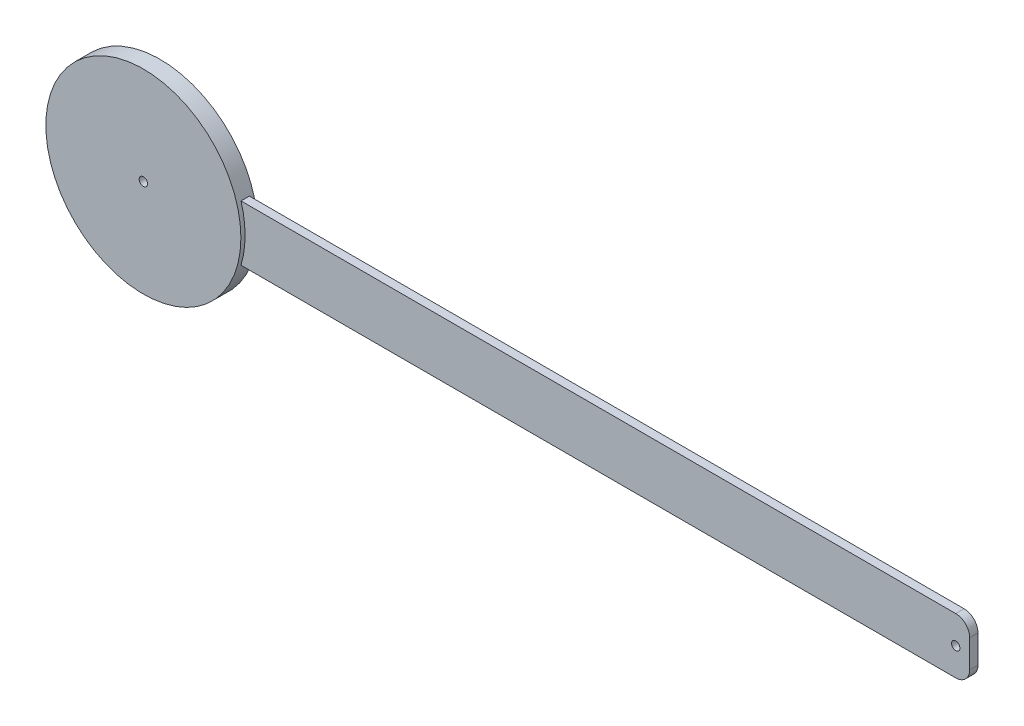
SolidWorks part; units mm, degrees
ref_plane "Front Plane" through (0, 0, 0) normal (0, 0, 1) x (1, 0, 0)
ref_plane "Top Plane" through (0, 0, 0) normal (0, 1, 0) x (1, 0, 0)
ref_plane "Right Plane" through (0, 0, 0) normal (1, 0, 0) x (0, 0, -1)
sketch "Sketch1" plane through (0, 0, 0) normal (0, 0, 1) x (1, 0, 0)
  line L1 (-145, 10) -> (145, 10)
  line L2 (-150, 5) -> (-150, -5)
  line L3 (-145, -10) -> (145, -10)
  line L4 (150, 5) -> (150, -5)
  line L5 (-150, 10) -> (150, -10) construction
  line L6 (-150, -10) -> (150, 10) construction
  arc A0 (145, 10) -> (150, 5) centre (145, 5) cw
  arc A1 (145, -10) -> (150, -5) centre (145, -5) ccw
  arc A2 (-150, -5) -> (-145, -10) centre (-145, -5) ccw
  arc A3 (-145, 10) -> (-150, 5) centre (-145, 5) ccw
  circle A4 centre (145, 0) radius 1.5
  point P0 (0, 0)
  point P20 (150, 0)
  dimension "D3" = 5
  dimension "D4" = 3
  dimension "D1" = 300
  dimension "D2" = 20
  dimension "D5" = 5
extrude "Boss-Extrude1" add sketch "Sketch1" along normal blind 3
hole_wizard "1/4-20 Tapped Hole1" [suppressed] positions "Sketch2" profile "Sketch3" tap size "1/4-20" standard "ANSI Inch"
sketch "Sketch2" plane through (0, 0, 3) normal (0, 0, 1) x (1, 0, 0)
  line L0 (150, -5) -> (150, 5) construction
  line L1 (-150, 5) -> (-150, -5) construction
  point P0 (145, 0)
  point P5 (150, 0)
  point P6 (-145, 0)
  dimension "D1" = 5
  dimension "D2" = 5
cosmetic thread "Hole Thread1" [suppressed] parameters "D1"=3, "D2"=6.35
cosmetic thread "Hole Thread3" [suppressed] parameters "D1"=4.5, "D2"=6.35
sketch "Sketch3" plane through (145, 0, 3) normal (1, 0, 0) x (0, -1, 0)
  line L0 (0, 0) -> (0, 3)
  line L1 (0, 3) -> (2.5527, 3)
  line L2 (2.5527, 3) -> (2.5527, 0)
  line L5 (2.5527, 0) -> (0, 0)
  line L11 (0, -6.35) -> (0, 107.95) construction
  dimension "Thru Tap Drill Dia." = 5.1054
  dimension "Thru Tap Drill Depth" = 3
sketch "Sketch4" plane through (0, 0, 0) normal (0, 0, 1) x (1, 0, 0)
  line L0 (-150, 5) -> (-150, -5) construction
  circle A0 centre (-145, 0) radius 35
  point P5 (-150, 0)
  dimension "D1" = 70
extrude "Boss-Extrude2" add sketch "Sketch4" along normal blind 3 and the other way blind 3 from offset 1.5
hole_wizard "1/4-20 Tapped Hole2" [suppressed] positions "Sketch7" profile "Sketch8" tap size "1/4-20" standard "ANSI Inch"
sketch "Sketch7" plane through (0, 0, 4.5) normal (0, 0, 1) x (1, 0, 0)
  point P0 (-145, 0)
sketch "Sketch8" plane through (-145, 0, 4.5) normal (1, 0, 0) x (0, -1, 0)
  line L0 (0, 0) -> (0, 6)
  line L1 (0, 6) -> (2.5527, 6)
  line L2 (2.5527, 6) -> (2.5527, 0)
  line L5 (2.5527, 0) -> (0, 0)
  line L11 (0, -6.35) -> (0, 107.95) construction
  dimension "Thru Tap Drill Dia." = 5.1054
  dimension "Thru Tap Drill Depth" = 6
cosmetic thread "Hole Thread4" [suppressed] parameters "D2"=6.35
sketch "Sketch9" plane through (0, 0, 4.5) normal (0, 0, 1) x (1, 0, 0)
  circle A0 centre (-145, 0) radius 1.5
  point P2 (0, 0)
  dimension "D1" = 3
extrude "Cut-Extrude1" cut sketch "Sketch9" against normal through all
